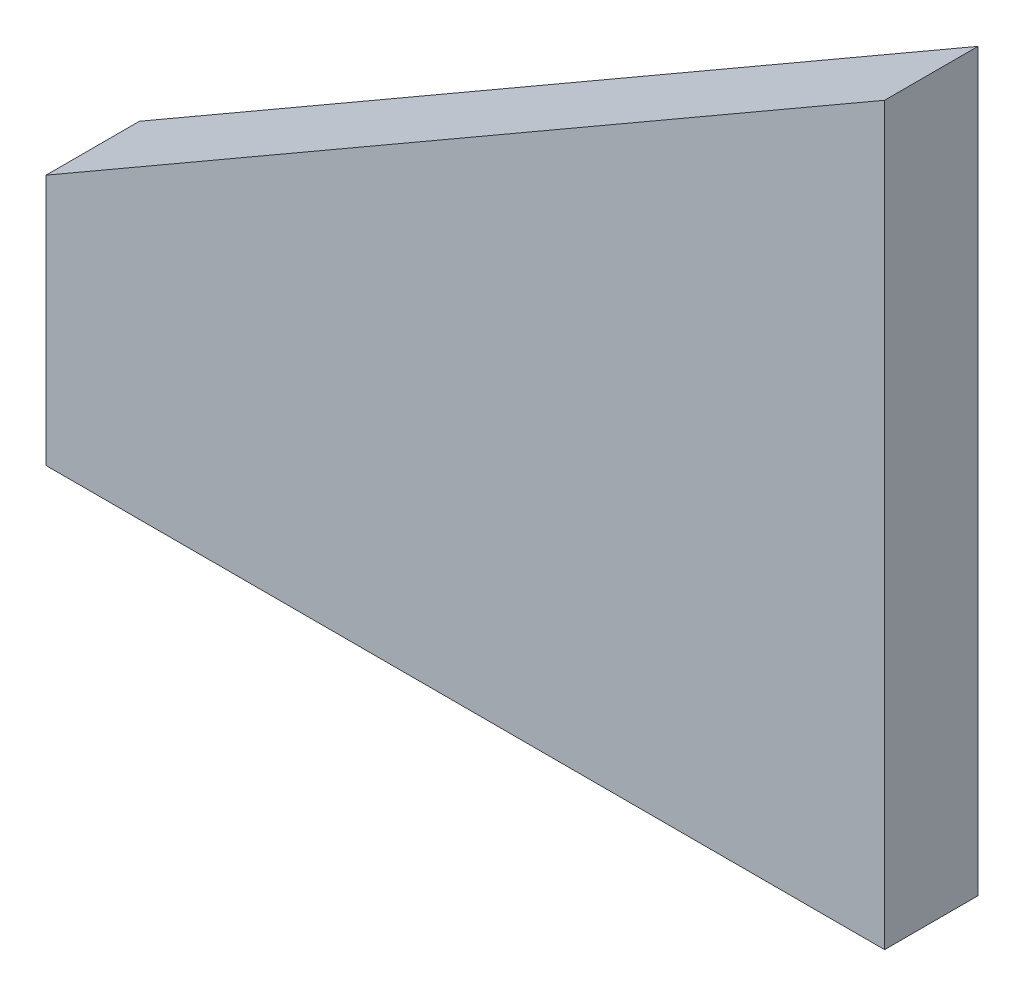
SolidWorks part; units mm, degrees
ref_plane "Front Plane" through (0, 0, 0) normal (0, 0, 1) x (1, 0, 0)
ref_plane "Top Plane" through (0, 0, 0) normal (0, 1, 0) x (1, 0, 0)
ref_plane "Right Plane" through (0, 0, 0) normal (1, 0, 0) x (0, 0, -1)
sketch "Sketch1" plane through (0, 0, 0) normal (0, 0, 1) x (1, 0, 0)
  line L0 (0, 0) -> (0, -100)
  line L1 (0, -100) -> (-114, -100)
  line L2 (-114, -65.8179) -> (0, 0)
  line L3 (-114, -65.8179) -> (-114, -100)
  dimension "D1" = 114
  dimension "D2" = 100
  dimension "D3" = 60
extrude "Boss-Extrude1" add sketch "Sketch1" along normal mid plane 12.7
